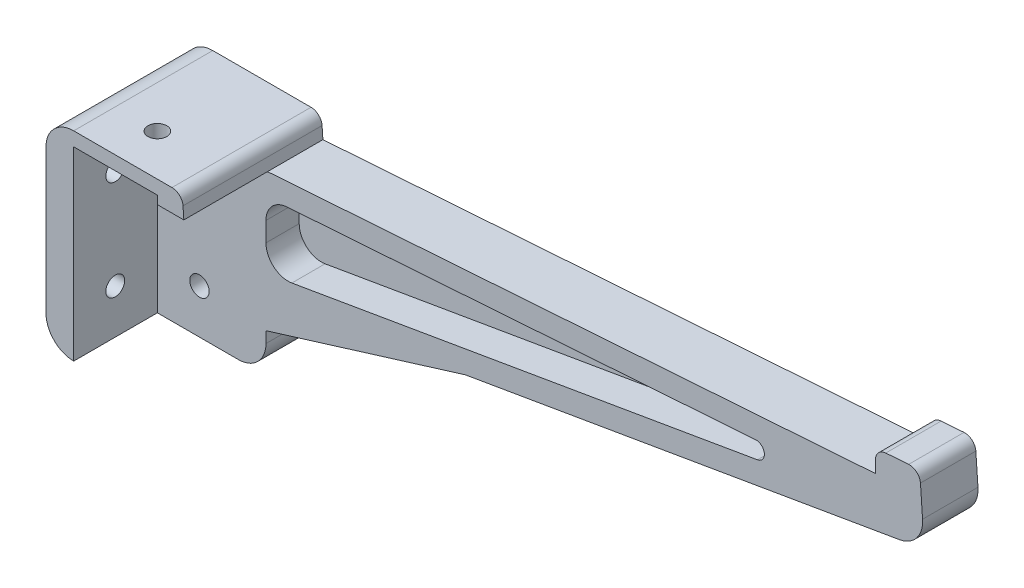
SolidWorks part; units mm, degrees
ref_plane "Front Plane" through (0, 0, 0) normal (0, 0, 1) x (1, 0, 0)
ref_plane "Top Plane" through (0, 0, 0) normal (0, 1, 0) x (1, 0, 0)
ref_plane "Right Plane" through (0, 0, 0) normal (1, 0, 0) x (0, 0, -1)
sketch "Sketch1" plane through (0, 0, 0) normal (0, 0, 1) x (1, 0, 0)
  line L0 (-7.6, 10) -> (10.135, 10)
  line L1 (12.1301, 8.1395) -> (12.279, 6.0097)
  line L2 (12.279, 6.0097) -> (122.0111, 13.683)
  line L3 (122.0111, 13.683) -> (122.0111, 15.8277)
  line L4 (123.8716, 17.8228) -> (127.9965, 18.1113)
  line L5 (130.1311, 16.2556) -> (130.513, 10.7938)
  line L6 (12, -21) -> (12, -14.0586)
  line L7 (7, -26) -> (-7.6, -26)
  line L8 (-12.6, -21) -> (-12.6, 5)
  line L9 (12, -14.0586) -> (126.3687, 5.5166)
  circle A0 centre (0, 0) radius 1.75
  circle A1 centre (0, -18) radius 1.75
  arc A2 (130.513, 10.7938) -> (126.3687, 5.5166) centre (125.5252, 10.445) cw
  arc A3 (12, -21) -> (7, -26) centre (7, -21) cw
  arc A4 (-7.6, -26) -> (-12.6, -21) centre (-7.6, -21) cw
  arc A5 (-7.6, 10) -> (-12.6, 5) centre (-7.6, 5) ccw
  arc A6 (127.9965, 18.1113) -> (130.1311, 16.2556) centre (128.136, 16.1161) cw
  arc A7 (122.0111, 15.8277) -> (123.8716, 17.8228) centre (124.0111, 15.8277) cw
  arc A8 (10.135, 10) -> (12.1301, 8.1395) centre (10.135, 8) cw
  point P17 (130.8287, 6.28)
  point P20 (12, -26)
  point P25 (-12.6, 10)
  point P28 (129.9916, 18.2508)
  point P31 (122.0111, 17.6927)
  point P34 (12, 10)
  dimension "D2" = 3.5
  dimension "D13" = 5
  dimension "D14" = 2
  dimension "D1" = 18
  dimension "D3" = 12
  dimension "D4" = 12.6
  dimension "D5" = 10
  dimension "D6" = 8
  dimension "D7" = 4
  dimension "D8" = 110
  dimension "D9" = 4
  dimension "D10" = 8
  dimension "D11" = 12
  dimension "D12" = 20
  dimension "D15" = 7.6
extrude "Boss-Extrude1" add sketch "Sketch1" along normal blind 10
sketch "Sketch2" plane through (0, 0, 10) normal (0, 0, 1) x (1, 0, 0)
  line L0 (12, -5.2576) -> (12, -1.7496)
  line L1 (15.721, 2.2407) -> (100.3595, 8.1592)
  line L2 (16.6748, -9.2003) -> (100.7172, 5.1843)
  line L3 (12, -14.0586) -> (126.3687, 5.5166) construction
  line L4 (122.0111, 13.683) -> (12.279, 6.0097) construction
  line L5 (12, -21) -> (12, -14.0586) construction
  arc A0 (100.7172, 5.1843) -> (100.3595, 8.1592) centre (100.4641, 6.6628) ccw
  arc A1 (16.6748, -9.2003) -> (12, -5.2576) centre (16, -5.2576) cw
  arc A2 (12, -1.7496) -> (15.721, 2.2407) centre (16, -1.7496) cw
  dimension "D1" = 1.5
  dimension "D4" = 4
  dimension "D2" = 4
  dimension "D3" = 4
extrude "Cut-Extrude1" cut sketch "Sketch2" against normal offset from surface (6 mm away) 4 up to face at (1.75, 0, 0)
sketch "Sketch4" plane through (0, 0, 10) normal (0, 0, 1) x (1, 0, 0)
  line L0 (12, -18.9903) -> (48, -7.8969)
  line L1 (12, -21) -> (12, -14.0586) construction
  line L2 (12, -14.0586) -> (126.3687, 5.5166) construction
  line L3 (48, -7.8969) -> (12, -14.0586)
  line L4 (12, -14.0586) -> (12, -18.9903)
  dimension "D1" = 25
  dimension "D2" = 36
extrude "Boss-Extrude2" add sketch "Sketch4" against normal up to surface (10 mm away) up to face at (1.75, 0, 0)
sketch "Sketch5" plane through (0, 0, 10) normal (0, 0, 1) x (1, 0, 0)
  line L0 (-7.6, 7.5) -> (-7.6, -26)
  line L1 (-12.6, -21) -> (-12.6, 5)
  line L2 (-7.6, 10) -> (10.135, 10)
  line L3 (7.5, 6.0097) -> (7.5, 7.5)
  line L4 (12.279, 6.0097) -> (12.1301, 8.1395) construction
  line L6 (7.5, 7.5) -> (-7.6, 7.5)
  line L9 (12.1301, 8.1395) -> (12.279, 6.0097)
  line L10 (12.279, 6.0097) -> (7.5, 6.0097)
  arc A0 (-12.6, 5) -> (-7.6, 10) centre (-7.6, 5) cw
  arc A1 (-12.6, -21) -> (-7.6, -26) centre (-7.6, -21) ccw
  arc A2 (10.135, 10) -> (12.1301, 8.1395) centre (10.135, 8) cw
  circle A3 centre (0, -18) radius 1.75 construction
  dimension "D1" = 7.6
  dimension "D2" = 2.5
  dimension "D3" = 15.1
extrude "Boss-Extrude3" add sketch "Sketch5" along normal blind 15.1
hole_wizard "M3 Clearance Hole1" positions "Sketch7" profile "Sketch6" hole size "M3" standard "ANSI Metric" end condition through all
sketch "Sketch7" plane through (-7.6, 0, 0) normal (1, 0, 0) x (0, 0, -1)
  line L0 (-10, -26) -> (-10, 7.5) construction
  line L1 (-17.6, -18) -> (-17.6, 6.5454) construction
  line L3 (-25.1, -26) -> (-10, -26) construction
  point P0 (-17.6, -18)
  point P2 (-17.6, 0)
  point P15 (-17.55, -26)
  dimension "D1" = 7.6
  dimension "D2" = 8
  dimension "D3" = 18
sketch "Sketch6" plane through (-7.6, -18, 17.6) normal (0, 1, 0) x (0, 0, -1)
  line L0 (0, 0) -> (0, 5)
  line L1 (0, 5) -> (1.7, 5)
  line L2 (1.7, 5) -> (1.7, 0)
  line L5 (1.7, 0) -> (0, 0)
  line L11 (0, -6.35) -> (0, 107.95) construction
  dimension "Thru Hole Dia." = 3.4
  dimension "Thru Hole Depth" = 5
hole_wizard "M3 Clearance Hole2" positions "Sketch9" profile "Sketch8" hole size "M3" standard "ANSI Metric" end condition through all
sketch "Sketch9" plane through (0, 10, 0) normal (0, 1, 0) x (1, 0, 0)
  line L1 (-7.6, -10) -> (7.5, -10) construction
  line L2 (-7.6, -25.1) -> (-7.6, -10) construction
  point P0 (0, -17.6)
  point P6 (-0.05, -10)
  point P9 (-7.6, -17.55)
  dimension "D1" = 7.6
  dimension "D2" = 7.6
sketch "Sketch8" plane through (0, 10, 17.6) normal (1, 0, 0) x (0, 0, 1)
  line L0 (0, 0) -> (0, 36)
  line L1 (0, 36) -> (1.7, 36)
  line L2 (1.7, 36) -> (1.7, 0)
  line L5 (1.7, 0) -> (0, 0)
  line L11 (0, -6.35) -> (0, 107.95) construction
  dimension "Thru Hole Dia." = 3.4
  dimension "Thru Hole Depth" = 36
